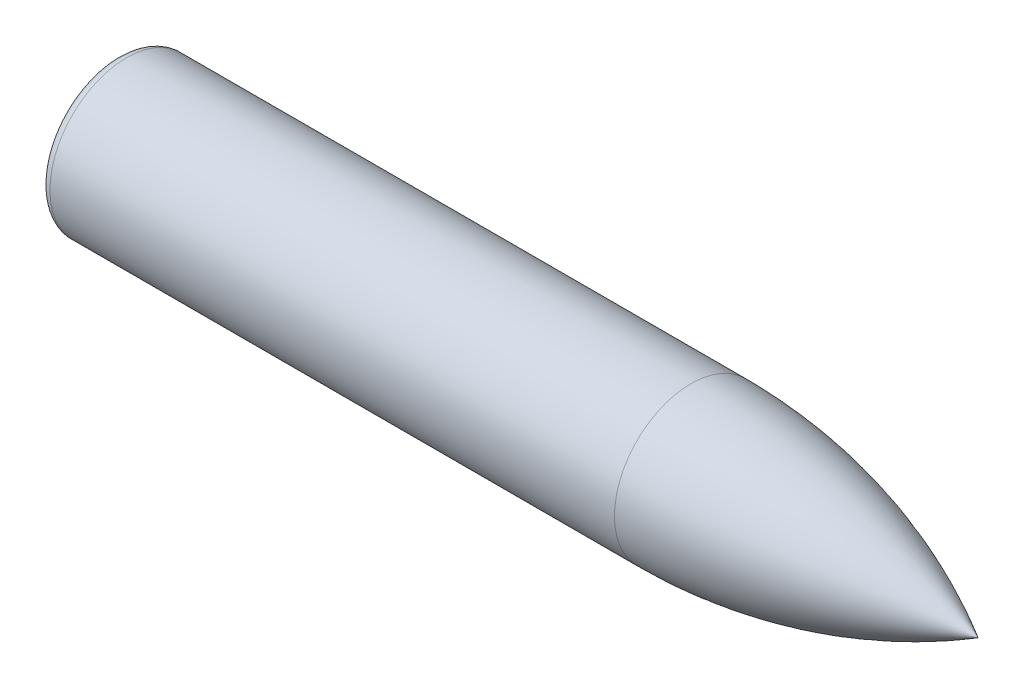
SolidWorks part; units mm, degrees
ref_plane "Front Plane" through (0, 0, 0) normal (0, 0, 1) x (1, 0, 0)
ref_plane "Top Plane" through (0, 0, 0) normal (0, 1, 0) x (1, 0, 0)
ref_plane "Right Plane" through (0, 0, 0) normal (1, 0, 0) x (0, 0, -1)
sketch "Çizim1" plane through (0, 0, 0) normal (0, 0, 1) x (1, 0, 0)
  line L0 (0, 0) -> (0, 160)
  line L1 (0, 160) -> (1200, 160)
  line L2 (0, 0) -> (1800, 0)
  arc A0 (1200, 160) -> (1800, 0) centre (1200, -1045) cw
  dimension "D1" = 160
  dimension "D2" = 1800
  dimension "D3" = 600
revolve "Döndür1" add sketch "Çizim1" angle 360 about L2
fillet "Radyus1" radius 20 1 edges at (0, 0, 160)
scale "Ölçek2" scale about centroid uniform scaling yes scale factor 1
